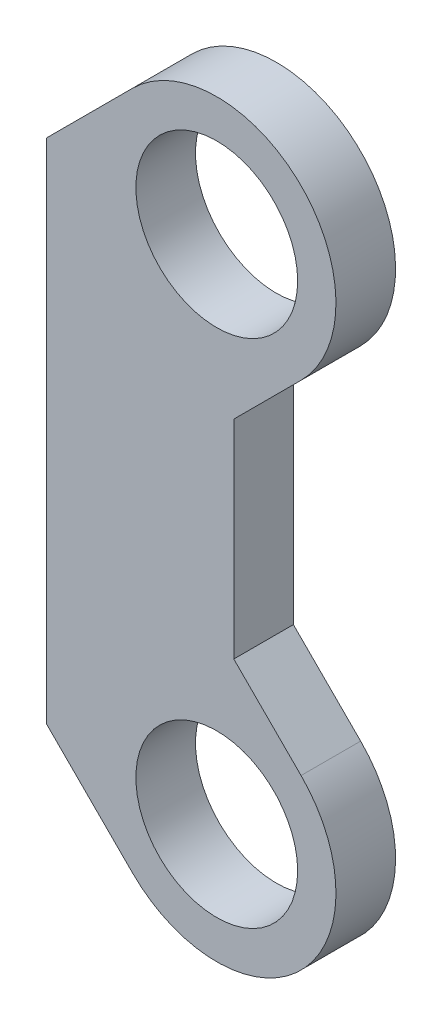
SolidWorks part; units mm, degrees
ref_plane "Alzado" through (0, 0, 0) normal (0, 0, 1) x (1, 0, 0)
ref_plane "Planta" through (0, 0, 0) normal (0, 1, 0) x (1, 0, 0)
ref_plane "Vista lateral" through (0, 0, 0) normal (1, 0, 0) x (0, 0, -1)
sketch "Croquis1" plane through (0, 0, 0) normal (0, 0, 1) x (1, 0, 0)
  line L0 (0, 0) -> (0, 30) construction
  line L1 (0, 0) -> (-6, 6) construction
  line L2 (-6, 6) -> (-6, 24) construction
  line L3 (-6, 24) -> (0, 30) construction
  line L4 (4.9497, 4.9497) -> (1, 8.8995)
  line L5 (1, 8.8995) -> (1, 21.1005)
  line L6 (1, 21.1005) -> (4.9497, 25.0503)
  line L7 (-4.9497, -4.9497) -> (-13, 3.1005)
  line L8 (-13, 3.1005) -> (-13, 26.8995)
  line L9 (-13, 26.8995) -> (-4.9497, 34.9497)
  circle A0 centre (0, 0) radius 4.75
  circle A1 centre (0, 0) radius 7
  circle A4 centre (0, 30) radius 4.75
  circle A5 centre (0, 30) radius 7
  dimension "D1" = 9.5
  dimension "D2" = 14
  dimension "D3" = 9.5
  dimension "D4" = 14
  dimension "D5" = 30
  dimension "D6" = 45
  dimension "D7" = 45
  dimension "D8" = 18
  dimension "D9" = 7
  dimension "D10" = 7
extrude "Saliente-Extruir1" add sketch "Croquis1" along normal blind 3.5 contours A5 L9 L8 L7 A1 L4 L5 L6 | A5 A4 | A1 A0
sketch "Croquis4" plane through (0, 0, 3.5) normal (0, 0, 1) x (1, 0, 0)
  line L0 (1, 15) -> (-13, 15)
  line L1 (1, 8.8995) -> (1, 21.1005) construction
  line L2 (-13, 3.1005) -> (-13, 26.8995) construction
  line L3 (-13, 26.8995) -> (-4.9497, 34.9497) construction
  line L4 (-10, 29.8995) -> (-18.2359, 29.8995)
  line L5 (-10, 29.8995) -> (-10, -2.6794)
  line L6 (-10, -2.6794) -> (-18.2359, -2.6794)
  line L7 (-18.2359, 29.8995) -> (-18.2359, -2.6794)
  dimension "D1" = 3
extrude "Cortar-Extruir4" cut sketch "Croquis4" against normal blind 4 contours L4 L7 L6 L5
